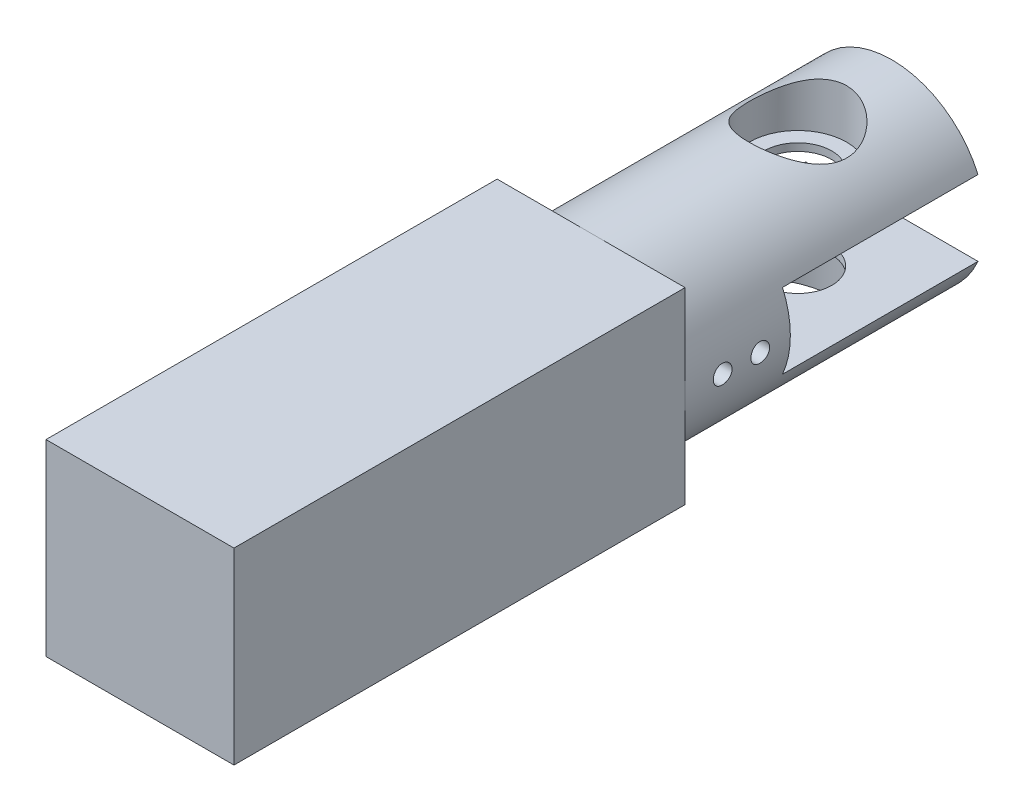
SolidWorks part; units mm, degrees
ref_plane "정면" through (0, 0, 0) normal (0, 0, 1) x (1, 0, 0)
ref_plane "윗면" through (0, 0, 0) normal (0, 1, 0) x (1, 0, 0)
ref_plane "우측면" through (0, 0, 0) normal (1, 0, 0) x (0, 0, -1)
sketch "스케치1" plane through (0, 0, 0) normal (0, 0, 1) x (1, 0, 0)
  circle A0 centre (0, 0) radius 12.5
  dimension "D1" = 25
extrude "보스-돌출1" add sketch "스케치1" against normal blind 100 contours A0
sketch "스케치2" plane through (0, 0, -100) normal (0, 0, -1) x (-1, 0, 0)
  line L0 (18.4039, 0) -> (-28.4221, 0) construction
  line L2 (11.4564, 5) -> (-11.4564, 5)
  line L4 (11.4564, -5) -> (-11.4564, -5)
  circle A1 centre (0, 0) radius 12.5 construction
  arc A5 (11.4564, -5) -> (11.4564, 5) centre (0, 0) ccw
  circle A6 centre (0, 0) radius 12.5
  arc A7 (-11.4564, 5) -> (-11.4564, -5) centre (0, 0) ccw
  dimension "D2" = 5
  dimension "D1" = 0
extrude "컷-돌출1" cut sketch "스케치2" against normal blind 26
ref_plane "평면2" through (12.5, 0, 0) normal (1, 0, 0) x (0, 0, -1)
sketch "스케치3" plane through (0, 0, 0) normal (0, 1, 0) x (1, 0, 0)
  line L0 (25.0967, 87.5) -> (-34.827, 87.5) construction
  line L2 (12.5, 0) -> (12.5, 74) construction
  line L3 (12.5, -11.7673) -> (12.5, 74) construction
  line L6 (12.5, 74) -> (11.4564, 74) construction
  circle A0 centre (0, 87.5) radius 4.5
  dimension "D1" = 9
  dimension "D2" = 13.5
extrude "컷-돌출2" cut sketch "스케치3" against normal blind 36.5348 and the other way blind 34
ref_plane "평면3" through (0, 6, 0) normal (0, -1, 0) x (-1, 0, 0)
sketch "스케치6" plane through (0, 6, 0) normal (0, 1, 0) x (1, 0, 0)
  circle A0 centre (0, 87.5) radius 6.5
  dimension "D1" = 13
extrude "컷-돌출5" cut sketch "스케치6" along normal blind 16
mirror "대칭 복사1" about plane through (0, 0, 0) normal (0, 1, 0) of "컷-돌출5"
sketch "스케치7" plane through (0, 0, -74) normal (0, 0, -1) x (-1, 0, 0)
  line L5 (-9, -2.5) -> (9, -2.5)
  line L6 (-9, -2.5) -> (-9, 2.5)
  line L7 (-9, 2.5) -> (9, 2.5)
  line L8 (9, -2.5) -> (9, 2.5)
  line L9 (-9, -2.5) -> (9, 2.5) construction
  line L10 (-9, 2.5) -> (9, -2.5) construction
  point P0 (0, 0)
  point P6 (9, 0.944)
  point P11 (0, 0)
  dimension "D1" = 5
  dimension "D2" = 18
extrude "컷-돌출6" cut sketch "스케치7" against normal blind 13
sketch "스케치9" plane through (12.5, 0, 0) normal (1, 0, 0) x (0, 0, -1)
  line L0 (74, -5) -> (74, 5) construction
  line L2 (61, 2.5) -> (61, -2.5) construction
  circle A0 centre (70, 0) radius 1.25
  circle A1 centre (65, 0) radius 1.25
  point P6 (62.4623, 0)
  dimension "D1" = 2.5
  dimension "D2" = 4
  dimension "D3" = 4
extrude "컷-돌출7" cut sketch "스케치9" against normal blind 44
sketch "스케치10" plane through (0, 0, 0) normal (0, 0, 1) x (1, 0, 0)
  line L1 (-12.5, -12.5) -> (12.5, -12.5)
  line L2 (-12.5, -12.5) -> (-12.5, 12.5)
  line L3 (-12.5, 12.5) -> (12.5, 12.5)
  line L4 (12.5, -12.5) -> (12.5, 12.5)
  line L5 (-12.5, -12.5) -> (12.5, 12.5) construction
  line L6 (-12.5, 12.5) -> (12.5, -12.5) construction
  point P0 (0, 0)
extrude "보스-돌출2" add sketch "스케치10" against normal blind 60
